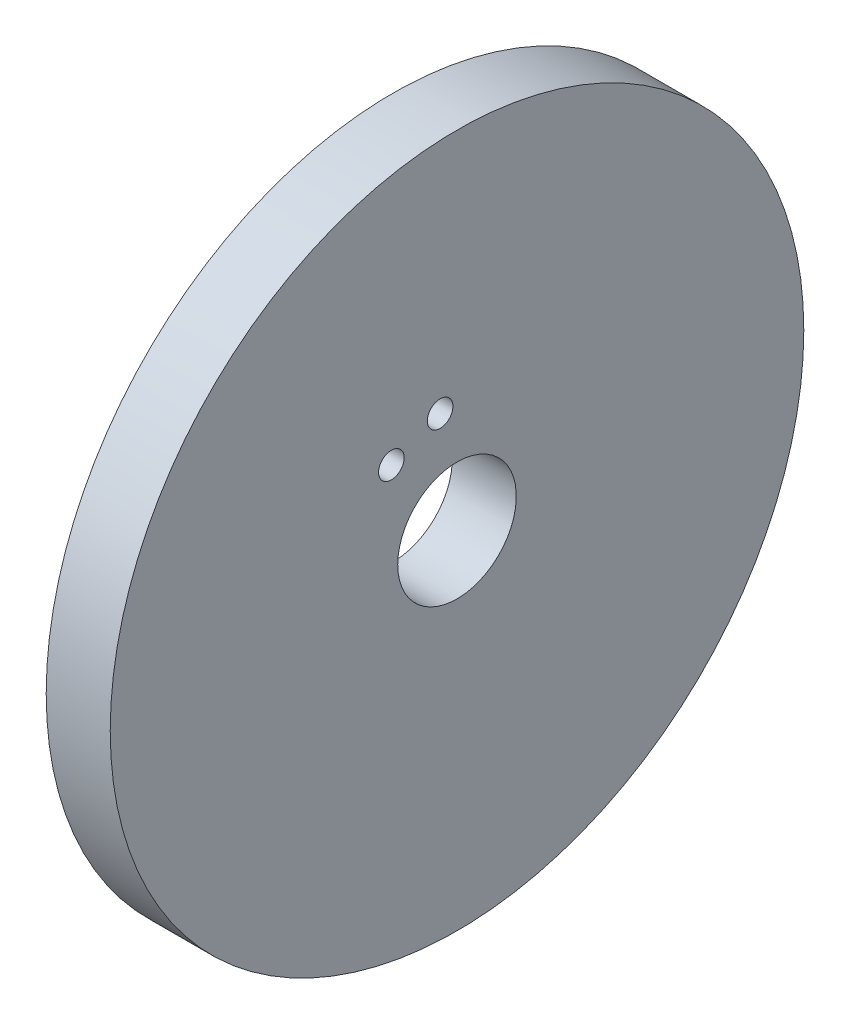
SolidWorks part; units mm, degrees
ref_plane "Front Plane" through (0, 0, 0) normal (0, 0, 1) x (1, 0, 0)
ref_plane "Top Plane" through (0, 0, 0) normal (0, 1, 0) x (1, 0, 0)
ref_plane "Right Plane" through (0, 0, 0) normal (1, 0, 0) x (0, 0, -1)
sketch "Axial profile (mm)" plane through (0, 0, 0) normal (0, 0, 1) x (1, 0, 0)
  line L0 (-110, 0) -> (75, 0) construction
  line L1 (13.7, 11.1125) -> (25.7, 11.1125)
  line L2 (25.7, 11.1125) -> (25.7, 65)
  line L3 (25.7, 65) -> (13.7, 65)
  line L4 (13.7, 65) -> (13.7, 11.1125)
revolve "Full revolution" add sketch "Axial profile (mm)" angle 360 about L0
sketch "Sketch2" plane through (0, 0, 0) normal (1, 0, 0) x (0, 0, -1)
  circle A0 centre (-3.1638, 20.558) radius 2.4
  circle A1 centre (-12.2995, 16.7738) radius 2.4
extrude "Axial holes" cut sketch "Sketch2" along normal through all and the other way through all
sketch "Sketch3" plane through (0, 0, 0) normal (1, 0, 0) x (0, 0, -1)
  circle A0 centre (-34.6482, 34.6482) radius 1.3
  circle A1 centre (-34.6482, -34.6482) radius 1.3
  circle A2 centre (34.6482, -34.6482) radius 1.3
  circle A3 centre (34.6482, 34.6482) radius 1.3
extrude "Cut-Extrude2" cut sketch "Sketch3" along normal blind 7 from offset 13.7
